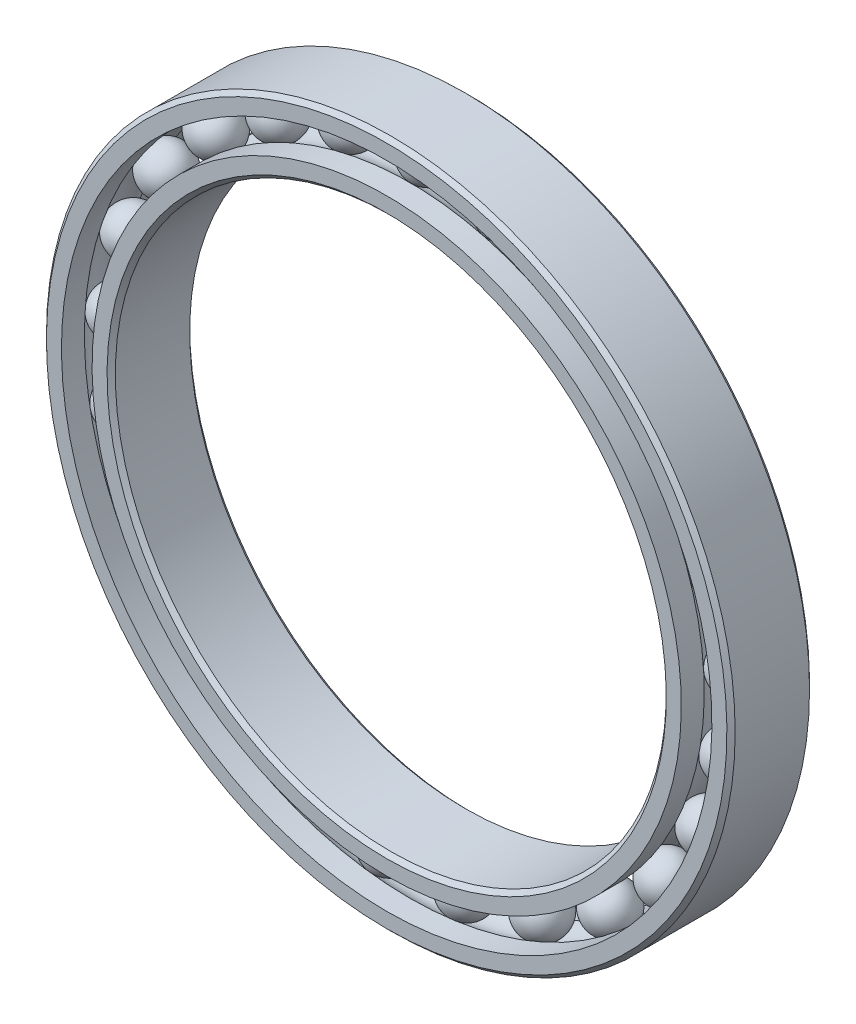
SolidWorks part; units mm, degrees
ref_plane "Front Plane" through (0, 0, 0) normal (0, 0, 1) x (1, 0, 0)
ref_plane "Top Plane" through (0, 0, 0) normal (0, 1, 0) x (1, 0, 0)
ref_plane "Right Plane" through (0, 0, 0) normal (1, 0, 0) x (0, 0, -1)
sketch "Sketch1" plane through (0, 0, 0) normal (0, 0, 1) x (1, 0, 0)
  circle A0 centre (0, 0) radius 25
  circle A1 centre (0, 0) radius 20
  dimension "OD" = 50
  dimension "ID" = 40
  dimension "For Shaft Diameter" = 40
  dimension "For Housing ID" = 50
sketch "Sketch5" plane through (0, 0, 0) normal (1, 0, 0) x (0, 0, -1)
  line L0 (-3, 0) -> (3, 0) construction
  line L1 (0, 25) -> (0, -25) construction
  line L2 (2.7, 25) -> (-2.7, 25)
  line L3 (-2.7, 25) -> (-3, 24.7)
  line L4 (-3, 24.7) -> (-3, 23.6111)
  line L5 (-3, 23.6111) -> (-1.3333, 23.6111)
  line L6 (3, 23.6111) -> (1.3333, 23.6111)
  line L7 (3, 24.7) -> (3, 23.6111)
  line L8 (2.7, 25) -> (3, 24.7)
  line L9 (0, 25) -> (0, 22.5) construction
  line L10 (0, 22.5) -> (0, 20) construction
  line L11 (-1.7356, 22.5) -> (-3, 22.5) construction
  line L12 (2.1773, 21.4143) -> (2.5583, 21.4143) construction
  line L13 (-2.1773, 21.4143) -> (-2.5583, 21.4143) construction
  line L14 (-2.1773, 21.4143) -> (-2.1773, 23.5857) construction
  line L15 (-2.1773, 23.5857) -> (-2.5583, 23.5857) construction
  line L16 (-2.5583, 21.4143) -> (-2.5583, 23.5857) construction
  line L17 (-2.1773, 21.4143) -> (-2.5583, 23.5857) construction
  line L18 (-2.1773, 23.5857) -> (-2.5583, 21.4143) construction
  line L19 (2.5583, 21.4143) -> (2.5583, 23.5857) construction
  line L20 (2.1773, 23.5857) -> (2.5583, 23.5857) construction
  line L21 (2.1773, 21.4143) -> (2.1773, 23.5857) construction
  line L22 (0, 25) -> (0, -25) construction
  arc A0 (-1.3333, 23.6111) -> (1.3333, 23.6111) centre (0, 22.5) cw
  circle A1 centre (0, 22.5) radius 1.7356 construction
  point P14 (0, 20)
  point P15 (-2.3678, 22.5)
  dimension "D1" = 45
  dimension "D2" = 0.3
  dimension "D3" = 2.6667
  dimension "D4" = 1.1111
  dimension "D5" = 0.381
  dimension "D6" = 0.0254
  dimension "Width" = 6
sketch "Sketch6" plane through (0, 0, 0) normal (1, 0, 0) x (0, 0, -1)
  line L0 (2.7, 25) -> (3, 24.7) construction
  line L1 (3, 24.7) -> (3, 23.6111) construction
  line L2 (3, 23.6111) -> (1.3333, 23.6111) construction
  line L3 (-3, 23.6111) -> (-1.3333, 23.6111) construction
  line L4 (-3, 24.7) -> (-3, 23.6111) construction
  line L5 (-2.7, 25) -> (-3, 24.7) construction
  line L6 (2.7, 25) -> (-2.7, 25) construction
  line L7 (2.7, 25) -> (3, 24.7)
  line L8 (3, 24.7) -> (3, 23.6111)
  line L9 (3, 23.6111) -> (1.3333, 23.6111)
  line L10 (-3, 23.6111) -> (-1.3333, 23.6111)
  line L11 (-3, 24.7) -> (-3, 23.6111)
  line L12 (-2.7, 25) -> (-3, 24.7)
  line L13 (2.7, 25) -> (-2.7, 25)
  arc A0 (1.3333, 23.6111) -> (-1.3333, 23.6111) centre (0, 22.5) ccw construction
  arc A1 (1.3333, 23.6111) -> (-1.3333, 23.6111) centre (0, 22.5) ccw
revolve "Revolve5" add sketch "Sketch6" angle 360 about L0
sketch "Sketch3" plane through (0, 0, 0) normal (1, 0, 0) x (0, 0, -1)
  line L0 (-3, 21.3889) -> (-1.3333, 21.3889)
  line L1 (0, 25) -> (0, -25) construction
  line L2 (-3, 24.7) -> (-3, 23.6111) construction
  line L3 (-3, 21.3889) -> (-3, 20.3)
  line L4 (-2.7, 25) -> (-3, 24.7) construction
  line L5 (-3, 20.3) -> (-2.7, 20)
  line L6 (-2.7, 20) -> (2.7, 20)
  line L8 (2.7, 20) -> (3, 20.3)
  line L10 (3, 20.3) -> (3, 21.3889)
  line L11 (3, 21.3889) -> (1.3333, 21.3889)
  line L12 (2.7, 25) -> (2.7, -25) construction
  line L13 (2.7, 25) -> (3, 24.7) construction
  line L14 (3, -24.7) -> (3, 24.7) construction
  arc A0 (1.3333, 23.6111) -> (-1.3333, 23.6111) centre (0, 22.5) ccw construction
  arc A1 (1.3333, 21.3889) -> (-1.3333, 21.3889) centre (0, 22.5) cw
revolve "Revolve3" add sketch "Sketch3" angle 360 about L0
sketch "Sketch4" plane through (0, 0, 0) normal (1, 0, 0) x (0, 0, -1)
  line L0 (-1.7356, 22.5) -> (1.7356, 22.5)
  arc A2 (-1.7356, 22.5) -> (1.7356, 22.5) centre (0, 22.5) cw
  arc A3 (1.3333, 23.6111) -> (-1.3333, 23.6111) centre (0, 22.5) ccw construction
revolve "Revolve4" add sketch "Sketch4" angle 360 about L0
pattern_circular "CirPattern1" count 25 over 360 about axis through (0, 0, 0) along (0, 0, 1) of bodies 104
equation "\"D2@Sketch5\" = \"Width@Sketch5\" * .05"
equation "\"D3@Sketch5\" = \"Width@Sketch5\" / 2.25"
equation "\"D4@Sketch5\"=((\"OD@Sketch1\"-\"ID@Sketch1\")/2)/4.5"
